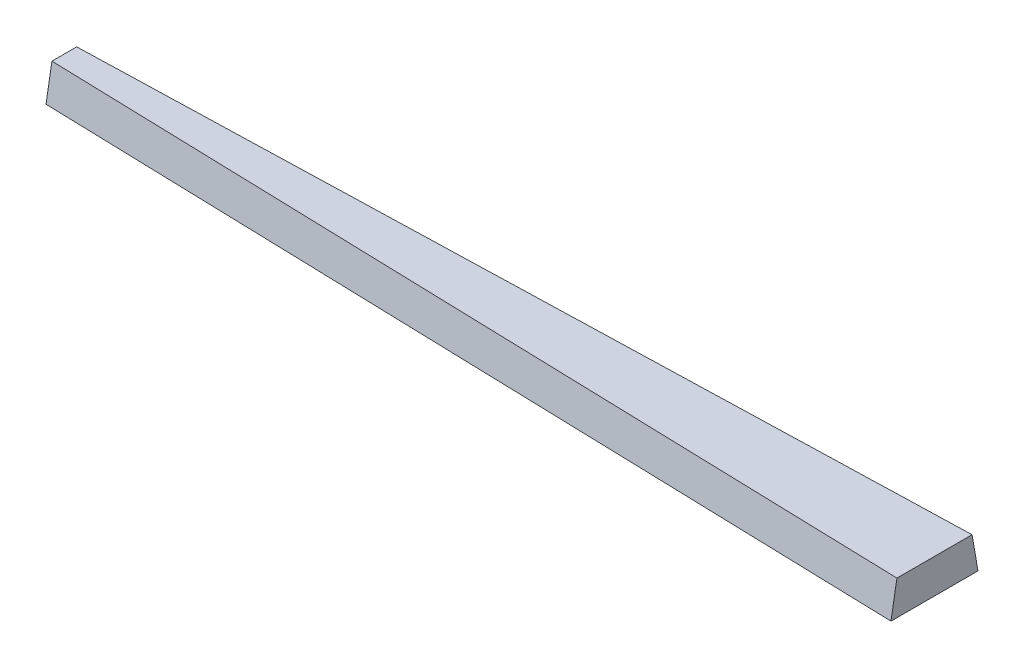
SolidWorks part; units mm, degrees
ref_plane "Front Plane" through (0, 0, 0) normal (0, 0, 1) x (1, 0, 0)
ref_plane "Top Plane" through (0, 0, 0) normal (0, 1, 0) x (1, 0, 0)
ref_plane "Right Plane" through (0, 0, 0) normal (1, 0, 0) x (0, 0, -1)
sketch "Sketch1" plane through (0, 0, 0) normal (0, 1, 0) x (1, 0, 0)
  line L1 (-241.3, -25.4) -> (241.3, -25.4)
  line L2 (-241.3, -25.4) -> (-241.3, 25.4)
  line L3 (-241.3, 25.4) -> (241.3, 25.4)
  line L4 (241.3, -25.4) -> (241.3, 25.4)
  line L5 (-241.3, -25.4) -> (241.3, 25.4) construction
  line L6 (-241.3, 25.4) -> (241.3, -25.4) construction
  point P0 (0, 0)
  dimension "D1" = 50.8
  dimension "D2" = 482.6
extrude "Boss-Extrude1" add sketch "Sketch1" along normal blind 19.05
sketch "Sketch2" plane through (241.3, 0, 0) normal (1, 0, 0) x (0, 0, -1)
  line L3 (25.4, 19.05) -> (25.4, 0) construction
  line L8 (-20.8395, 19.05) -> (0, 19.05) construction
  line L11 (-25.4, 19.05) -> (25.4, 19.05) construction
  line L12 (0, 19.05) -> (0, 0) construction
  line L13 (0, 0) -> (-24.13, 0) construction
  line L14 (-25.4, 0) -> (25.4, 0) construction
  line L15 (-24.13, 0) -> (-20.8395, 19.05) construction
  dimension "D1" = 80.2
  dimension "D2" = 24.13
sketch "Sketch3" plane through (-241.3, 0, 0) normal (-1, 0, 0) x (0, 0, 1)
  line L4 (6.8695, 19.05) -> (0, 19.05) construction
  line L6 (0, 19.05) -> (0, 0) construction
  line L7 (0, 0) -> (10.16, 0) construction
  line L9 (10.16, 0) -> (6.8695, 19.05) construction
  line L11 (-25.4, 19.05) -> (25.4, 19.05) construction
  line L12 (-25.4, 0) -> (25.4, 0) construction
  dimension "D1" = 10.16
  dimension "D2" = 80.2
ref_plane "Plane1" through (-0.4815, 2.8733, 16.6348) normal (-0.0285, 0.1701, 0.985) x (0.9996, 0.005, 0.0281)
sketch "Sketch5" plane through (-0.4815, 2.8733, 16.6348) normal (-0.0285, 0.1701, 0.985) x (0.9996, 0.005, 0.0281)
  line L0 (0, 0) -> (0, 35.0975) construction
  line L1 (-254, 35.0975) -> (254, 35.0975)
  line L2 (-254, 35.0975) -> (-254, -15.7025)
  line L3 (-254, -15.7025) -> (254, -15.7025)
  line L4 (254, 35.0975) -> (254, -15.7025)
  dimension "D1" = 508
  dimension "D2" = 50.8
extrude "Cut-Extrude1" cut sketch "Sketch5" along normal through all
mirror "Mirror1" about plane through (0, 0, 0) normal (0, 0, 1) of "Cut-Extrude1"
